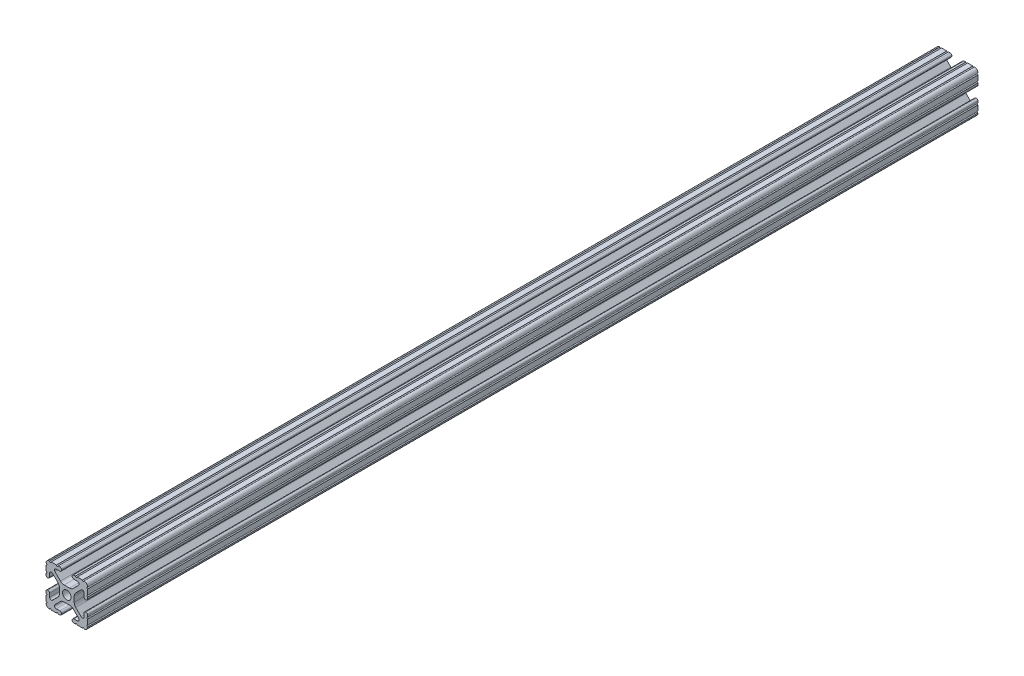
SolidWorks part; units mm, degrees
ref_plane "Front Plane" through (0, 0, 0) normal (0, 0, 1) x (1, 0, 0)
ref_plane "Top Plane" through (0, 0, 0) normal (0, 1, 0) x (1, 0, 0)
ref_plane "Right Plane" through (0, 0, 0) normal (1, 0, 0) x (0, 0, -1)
sketch "Sketch1" plane through (0, 0, 0) normal (0, 0, 1) x (1, 0, 0)
  line L88 (-7.1797, -8.6452) -> (-3.9523, -5.4237)
  line L89 (-1.7093, -4.4958) -> (1.7093, -4.4958)
  line L90 (3.9523, -5.4237) -> (7.1797, -8.6452)
  line L91 (6.4164, -10.4902) -> (4.2875, -10.4902)
  line L92 (3.2385, -11.5392) -> (3.2385, -11.651)
  line L93 (4.2875, -12.7) -> (5.3171, -12.7)
  line L94 (6.3331, -12.7) -> (9.5504, -12.7)
  line L95 (12.7, -9.5504) -> (12.7, -6.3331)
  line L96 (12.7, -5.3171) -> (12.7, -4.2875)
  line L97 (11.651, -3.2385) -> (11.5392, -3.2385)
  line L98 (10.4902, -4.2875) -> (10.4902, -6.4021)
  line L99 (8.7371, -7.1294) -> (5.441, -3.8408)
  line L100 (4.5085, -1.5932) -> (4.5085, 1.5932)
  line L101 (5.441, 3.8408) -> (8.7371, 7.1294)
  line L102 (10.4902, 6.4021) -> (10.4902, 4.2875)
  line L103 (11.5392, 3.2385) -> (11.651, 3.2385)
  line L104 (12.7, 4.2875) -> (12.7, 5.3171)
  line L105 (12.7, 6.3331) -> (12.7, 9.5504)
  line L106 (9.5504, 12.7) -> (6.3331, 12.7)
  line L107 (5.3171, 12.7) -> (4.2875, 12.7)
  line L108 (3.2385, 11.651) -> (3.2385, 11.5392)
  line L109 (4.2875, 10.4902) -> (6.4768, 10.4902)
  line L110 (7.207, 8.7244) -> (3.8983, 5.4232)
  line L111 (1.6558, 4.4958) -> (-1.6558, 4.4958)
  line L112 (-3.8983, 5.4232) -> (-7.207, 8.7244)
  line L113 (-6.4768, 10.4902) -> (-4.2875, 10.4902)
  line L114 (-3.2385, 11.5392) -> (-3.2385, 11.651)
  line L115 (-4.2875, 12.7) -> (-5.3171, 12.7)
  line L116 (-6.3331, 12.7) -> (-9.5504, 12.7)
  line L117 (-12.7, 9.5504) -> (-12.7, 6.3331)
  line L118 (-12.7, 5.3171) -> (-12.7, 4.2875)
  line L119 (-11.651, 3.2385) -> (-11.5392, 3.2385)
  line L120 (-10.4902, 4.2875) -> (-10.4902, 6.4021)
  line L121 (-8.7371, 7.1294) -> (-5.441, 3.8408)
  line L122 (-4.5085, 1.5932) -> (-4.5085, -1.5932)
  line L123 (-5.441, -3.8408) -> (-8.7371, -7.1294)
  line L124 (-10.4902, -6.4021) -> (-10.4902, -4.2875)
  line L125 (-11.5392, -3.2385) -> (-11.651, -3.2385)
  line L126 (-12.7, -4.2875) -> (-12.7, -5.3171)
  line L127 (-12.7, -6.3331) -> (-12.7, -9.5504)
  line L128 (-9.5504, -12.7) -> (-6.3331, -12.7)
  line L129 (-5.3171, -12.7) -> (-4.2875, -12.7)
  line L130 (-3.2385, -11.651) -> (-3.2385, -11.5392)
  line L131 (-4.2875, -10.4902) -> (-6.4164, -10.4902)
  circle A1 centre (0, 0) radius 2.6035
  arc A104 (-7.1797, -8.6452) -> (-6.4164, -10.4902) centre (-6.4164, -9.4098) ccw
  arc A105 (-1.7093, -4.4958) -> (-3.9523, -5.4237) centre (-1.7093, -7.6708) ccw
  arc A106 (3.9523, -5.4237) -> (1.7093, -4.4958) centre (1.7093, -7.6708) ccw
  arc A107 (6.4164, -10.4902) -> (7.1797, -8.6452) centre (6.4164, -9.4098) ccw
  arc A108 (4.2875, -10.4902) -> (3.2385, -11.5392) centre (4.2875, -11.5392) ccw
  arc A109 (3.2385, -11.651) -> (4.2875, -12.7) centre (4.2875, -11.651) ccw
  arc A110 (6.3331, -12.7) -> (5.3171, -12.7) centre (5.8251, -12.7) ccw
  arc A111 (10.5664, -12.6998) -> (9.5504, -12.7) centre (10.0584, -12.7) ccw
  arc A112 (10.5664, -12.6998) -> (12.6998, -10.5664) centre (10.5918, -10.5918) ccw
  arc A113 (12.7, -9.5504) -> (12.6998, -10.5664) centre (12.7, -10.0584) ccw
  arc A114 (12.7, -5.3171) -> (12.7, -6.3331) centre (12.7, -5.8251) ccw
  arc A115 (12.7, -4.2875) -> (11.651, -3.2385) centre (11.651, -4.2875) ccw
  arc A116 (11.5392, -3.2385) -> (10.4902, -4.2875) centre (11.5392, -4.2875) ccw
  arc A117 (8.7371, -7.1294) -> (10.4902, -6.4021) centre (9.4628, -6.4021) ccw
  arc A118 (4.5085, -1.5932) -> (5.441, -3.8408) centre (7.6835, -1.5932) ccw
  arc A119 (5.441, 3.8408) -> (4.5085, 1.5932) centre (7.6835, 1.5932) ccw
  arc A120 (10.4902, 6.4021) -> (8.7371, 7.1294) centre (9.4628, 6.4021) ccw
  arc A121 (10.4902, 4.2875) -> (11.5392, 3.2385) centre (11.5392, 4.2875) ccw
  arc A122 (11.651, 3.2385) -> (12.7, 4.2875) centre (11.651, 4.2875) ccw
  arc A123 (12.7, 6.3331) -> (12.7, 5.3171) centre (12.7, 5.8251) ccw
  arc A124 (12.6998, 10.5664) -> (12.7, 9.5504) centre (12.7, 10.0584) ccw
  arc A125 (12.6998, 10.5664) -> (10.5664, 12.6998) centre (10.5918, 10.5918) ccw
  arc A126 (9.5504, 12.7) -> (10.5664, 12.6998) centre (10.0584, 12.7) ccw
  arc A127 (5.3171, 12.7) -> (6.3331, 12.7) centre (5.8251, 12.7) ccw
  arc A128 (4.2875, 12.7) -> (3.2385, 11.651) centre (4.2875, 11.651) ccw
  arc A129 (3.2385, 11.5392) -> (4.2875, 10.4902) centre (4.2875, 11.5392) ccw
  arc A130 (7.207, 8.7244) -> (6.4768, 10.4902) centre (6.4768, 9.4563) ccw
  arc A131 (1.6558, 4.4958) -> (3.8983, 5.4232) centre (1.6558, 7.6708) ccw
  arc A132 (-3.8983, 5.4232) -> (-1.6558, 4.4958) centre (-1.6558, 7.6708) ccw
  arc A133 (-6.4768, 10.4902) -> (-7.207, 8.7244) centre (-6.4768, 9.4563) ccw
  arc A134 (-4.2875, 10.4902) -> (-3.2385, 11.5392) centre (-4.2875, 11.5392) ccw
  arc A135 (-3.2385, 11.651) -> (-4.2875, 12.7) centre (-4.2875, 11.651) ccw
  arc A136 (-6.3331, 12.7) -> (-5.3171, 12.7) centre (-5.8251, 12.7) ccw
  arc A137 (-10.5664, 12.6998) -> (-9.5504, 12.7) centre (-10.0584, 12.7) ccw
  arc A138 (-10.5664, 12.6998) -> (-12.6998, 10.5664) centre (-10.5918, 10.5918) ccw
  arc A139 (-12.7, 9.5504) -> (-12.6998, 10.5664) centre (-12.7, 10.0584) ccw
  arc A140 (-12.7, 5.3171) -> (-12.7, 6.3331) centre (-12.7, 5.8251) ccw
  arc A141 (-12.7, 4.2875) -> (-11.651, 3.2385) centre (-11.651, 4.2875) ccw
  arc A142 (-11.5392, 3.2385) -> (-10.4902, 4.2875) centre (-11.5392, 4.2875) ccw
  arc A143 (-8.7371, 7.1294) -> (-10.4902, 6.4021) centre (-9.4628, 6.4021) ccw
  arc A144 (-4.5085, 1.5932) -> (-5.441, 3.8408) centre (-7.6835, 1.5932) ccw
  arc A145 (-5.441, -3.8408) -> (-4.5085, -1.5932) centre (-7.6835, -1.5932) ccw
  arc A146 (-10.4902, -6.4021) -> (-8.7371, -7.1294) centre (-9.4628, -6.4021) ccw
  arc A147 (-10.4902, -4.2875) -> (-11.5392, -3.2385) centre (-11.5392, -4.2875) ccw
  arc A148 (-11.651, -3.2385) -> (-12.7, -4.2875) centre (-11.651, -4.2875) ccw
  arc A149 (-12.7, -6.3331) -> (-12.7, -5.3171) centre (-12.7, -5.8251) ccw
  arc A150 (-12.6998, -10.5664) -> (-12.7, -9.5504) centre (-12.7, -10.0584) ccw
  arc A151 (-12.6998, -10.5664) -> (-10.5664, -12.6998) centre (-10.5918, -10.5918) ccw
  arc A152 (-9.5504, -12.7) -> (-10.5664, -12.6998) centre (-10.0584, -12.7) ccw
  arc A153 (-5.3171, -12.7) -> (-6.3331, -12.7) centre (-5.8251, -12.7) ccw
  arc A154 (-4.2875, -12.7) -> (-3.2385, -11.651) centre (-4.2875, -11.651) ccw
  arc A155 (-3.2385, -11.5392) -> (-4.2875, -10.4902) centre (-4.2875, -11.5392) ccw
extrude "Boss-Extrude1" add sketch "Sketch1" along normal mid plane 542.925
